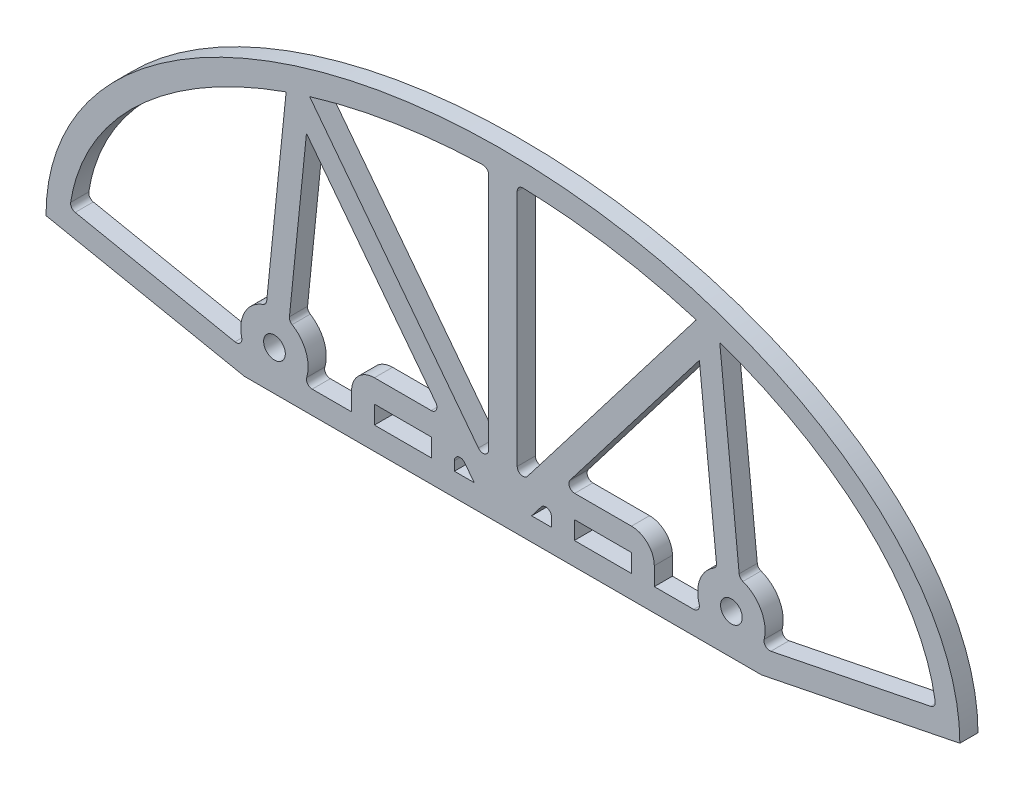
SolidWorks part; units mm, degrees
material "Birch Plywood"
ref_plane "Front Plane" through (0, 0, 0) normal (0, 0, 1) x (1, 0, 0)
ref_plane "Top Plane" through (0, 0, 0) normal (0, 1, 0) x (1, 0, 0)
ref_plane "Right Plane" through (0, 0, 0) normal (1, 0, 0) x (0, 0, -1)
sketch "Sketch3" plane through (0, 0, 0) normal (0, 0, 1) x (1, 0, 0)
  line L0 (85.2659, 27.2) -> (74.7341, 27.2) construction
  line L1 (74.7341, 27.2) -> (74.7341, 15.2) construction
  line L2 (74.7341, 15.2) -> (85.2659, 15.2) construction
  line L3 (85.2659, 15.2) -> (85.2659, 27.2) construction
  line L4 (5.2659, 27.2) -> (-5.2659, 27.2) construction
  line L5 (-5.2659, 27.2) -> (-5.2659, 15.2) construction
  line L6 (-5.2659, 15.2) -> (5.2659, 15.2) construction
  line L7 (5.2659, 15.2) -> (5.2659, 27.2) construction
  line L8 (85.2659, 27.2) -> (74.7341, 27.2) construction
  line L9 (74.7341, 27.2) -> (74.7341, 15.2) construction
  line L10 (74.7341, 15.2) -> (85.2659, 15.2) construction
  line L11 (85.2659, 15.2) -> (85.2659, 27.2) construction
  line L12 (5.2659, 27.2) -> (-5.2659, 27.2) construction
  line L13 (-5.2659, 27.2) -> (-5.2659, 15.2) construction
  line L14 (-5.2659, 15.2) -> (5.2659, 15.2) construction
  line L15 (5.2659, 15.2) -> (5.2659, 27.2) construction
  line L16 (0, 22.2) -> (80, 22.2) construction
  line L17 (-40, 22.2) -> (0, 22.2) construction
  line L18 (80, 22.2) -> (120, 22.2) construction
  line L19 (-40, 22.2) -> (-40, 72.2) construction
  line L20 (-40, 72.2) -> (40, 72.2) construction
  line L21 (-40, 22.2) -> (-5.2659, 15.2)
  line L22 (-5.2659, 15.2) -> (85.2659, 15.2)
  line L23 (85.2659, 15.2) -> (120, 22.2)
  line L24 (40, 72.2) -> (40, 15.2) construction
  line L25 (52.5, 22.375) -> (52.5, 19.2)
  line L26 (17.5, 22.375) -> (27.5, 22.375)
  line L27 (17.5, 22.375) -> (17.5, 19.2)
  line L28 (17.5, 19.2) -> (27.5, 19.2)
  line L29 (27.5, 22.375) -> (27.5, 19.2)
  line L30 (62.5, 19.2) -> (52.5, 19.2)
  line L31 (62.5, 22.375) -> (62.5, 19.2)
  line L32 (62.5, 22.375) -> (52.5, 22.375)
  circle A0 centre (80, 22.2) radius 1.9 construction
  circle A1 centre (0, 22.2) radius 1.9 construction
  circle A2 centre (80, 22.2) radius 1.9
  circle A3 centre (0, 22.2) radius 1.9
  ellipse E0 centre (40, 22.2) end of major axis (-40, 22.2) minor radius 50 (120, 22.2) -> (-40, 22.2) ccw
  dimension "D1" = 50
  dimension "D2" = 80
  dimension "D3" = 10
  dimension "D4" = 3.175
  dimension "D5" = 4
  dimension "D6" = 25
extrude "Boss-Extrude1" add sketch "Sketch3" along normal blind 3.175
sketch "Sketch4" plane through (0, 0, 3.175) normal (0, 0, 1) x (1, 0, 0)
  line L0 (-35.8077, 25.4355) -> (-5.1088, 19.2488)
  line L1 (5.0804, 19.2) -> (74.9196, 19.2)
  line L2 (85.1088, 19.2488) -> (115.8077, 25.4355)
  line L3 (85.2659, 15.2) -> (120, 22.2)
  line L4 (52.5, 22.375) -> (52.5, 19.2)
  line L5 (62.5, 22.375) -> (52.5, 22.375)
  line L6 (62.5, 19.2) -> (62.5, 22.375)
  line L7 (52.5, 19.2) -> (62.5, 19.2)
  line L8 (52.5, 22.375) -> (52.5, 19.2) construction
  line L9 (62.5, 22.375) -> (52.5, 22.375) construction
  line L10 (62.5, 19.2) -> (62.5, 22.375) construction
  line L11 (52.5, 19.2) -> (62.5, 19.2) construction
  line L12 (17.5, 19.2) -> (27.5, 19.2)
  line L13 (17.5, 22.375) -> (17.5, 19.2)
  line L14 (27.5, 22.375) -> (17.5, 22.375)
  line L15 (27.5, 19.2) -> (27.5, 22.375)
  line L16 (17.5, 19.2) -> (27.5, 19.2) construction
  line L17 (17.5, 22.375) -> (17.5, 19.2) construction
  line L18 (27.5, 22.375) -> (17.5, 22.375) construction
  line L19 (27.5, 19.2) -> (27.5, 22.375) construction
  line L20 (-40, 22.2) -> (-5.2659, 15.2)
  line L21 (-5.2659, 15.2) -> (85.2659, 15.2)
  line L22 (85.2659, 15.2) -> (120, 22.2) construction
  line L23 (-40, 22.2) -> (-5.2659, 15.2) construction
  line L24 (-5.2659, 15.2) -> (85.2659, 15.2) construction
  line L25 (17.5, 26.375) -> (27.5, 26.375)
  line L26 (13.5, 22.375) -> (13.5, 19.2)
  line L27 (31.5, 22.375) -> (31.5, 19.2)
  line L28 (40, 15.2) -> (40, 72.2) construction
  line L29 (48.5, 22.375) -> (48.5, 19.2)
  line L30 (62.5, 26.375) -> (52.5, 26.375)
  line L31 (66.5, 22.375) -> (66.5, 19.2)
  line L32 (-4.8669, 19.2) -> (84.8669, 19.2) construction
  line L33 (-35.8077, 25.4355) -> (-4.8669, 19.2) construction
  line L34 (84.8669, 19.2) -> (115.8077, 25.4355) construction
  line L35 (37.5, 68.2) -> (42.5, 68.2)
  line L36 (37.5, 68.2) -> (37.5, 19.2)
  line L37 (37.5, 19.2) -> (42.5, 19.2)
  line L38 (42.5, 68.2) -> (42.5, 19.2)
  line L39 (4.1233, 62.6899) -> (37.5, 19.2) construction
  line L40 (2.123, 62.0112) -> (34.9789, 19.2)
  line L41 (37.5, 22.485) -> (6.1527, 63.3306)
  line L42 (18.551, 40.6056) -> (21.7242, 43.0409) construction
  line L43 (0, 22.2) -> (4.1233, 62.6899) construction
  line L44 (2.0409, 61.9824) -> (-1.4274, 27.9247)
  line L45 (2.5521, 27.5195) -> (6.1935, 63.2774)
  line L46 (0.3068, 44.9535) -> (4.2862, 44.5483) construction
  line L47 (42.5, 19.2) -> (75.8767, 62.6899) construction
  line L48 (75.8767, 62.6899) -> (80, 22.2) construction
  line L49 (73.8473, 63.3306) -> (42.5, 22.485)
  line L50 (45.0211, 19.2) -> (77.877, 62.0112)
  line L51 (77.4479, 27.5195) -> (73.7996, 63.3451)
  line L52 (81.4274, 27.9247) -> (77.9591, 61.9824)
  line L53 (58.1737, 42.9078) -> (61.3469, 40.4725) construction
  line L54 (79.6932, 44.9535) -> (75.7138, 44.5483) construction
  line L55 (6.1935, 63.2774) -> (6.2004, 63.3451)
  arc A0 (85.1088, 19.2488) -> (74.9196, 19.2) centre (80, 22.2) ccw
  circle A1 centre (80, 22.2) radius 1.9
  circle A2 centre (80, 22.2) radius 1.9 construction
  circle A3 centre (0, 22.2) radius 1.9
  circle A4 centre (0, 22.2) radius 1.9 construction
  arc A5 (5.0804, 19.2) -> (-5.1088, 19.2488) centre (0, 22.2) ccw
  circle A7 centre (0, 22.2) radius 5.9 construction
  circle A8 centre (80, 22.2) radius 5.9 construction
  arc A10 (17.5, 26.375) -> (13.5, 22.375) centre (17.5, 22.375) ccw
  arc A11 (31.5, 22.375) -> (27.5, 26.375) centre (27.5, 22.375) ccw
  arc A12 (48.5, 22.375) -> (52.5, 26.375) centre (52.5, 22.375) cw
  arc A13 (62.5, 26.375) -> (66.5, 22.375) centre (62.5, 22.375) cw
  arc A14 (28.2377, 27.9838) -> (27.4444, 26.375) centre (27.4444, 27.375) cw
  arc A15 (33.2933, 21.3963) -> (31.5, 20.7875) centre (32.5, 20.7875) ccw
  arc A16 (48.5, 20.7875) -> (46.7067, 21.3963) centre (47.5, 20.7875) ccw
  arc A17 (52.5556, 26.375) -> (51.7623, 27.9838) centre (52.5556, 27.375) cw
  ellipse E1 centre (40, 22.2) end of major axis (-40, 22.2) minor radius 50 (120, 22.2) -> (-40, 22.2) ccw
  ellipse E2 centre (40, 22.2) end of major axis (-40, 22.2) minor radius 50 (120, 22.2) -> (-40, 22.2) ccw construction
  spline S0 degree 1 poles (115.8077, 25.4355) (-35.8077, 25.4355) knots 0 0 1 1 construction
  spline S1 degree 3 poles (115.8077, 25.4355) (115.6445, 26.8071) (115.1196, 29.5011) (113.2412, 34.9033) (109.3338, 41.5165) (102.177, 48.9647) (91.951, 56.1358) (83.1998, 60.1358) (77.9454, 61.9872) (77.9181, 61.9968) (77.8907, 62.0064) (77.6255, 62.0996) (77.1208, 62.2745) (76.2937, 62.5539) (75.4596, 62.8269) (74.6188, 63.0936) (74.105, 63.2522) (73.8394, 63.333) (73.8235, 63.3378) (73.8076, 63.3427) (71.9958, 63.8929) (63.5411, 66.2046) (49.7109, 68.2708) (30.2891, 68.2708) (16.4589, 66.2046) (8.0042, 63.8929) (6.1924, 63.3427) (6.1765, 63.3378) (6.1606, 63.333) (5.895, 63.2522) (5.3812, 63.0936) (4.5404, 62.8269) (3.7063, 62.5539) (2.8792, 62.2745) (2.3745, 62.0996) (2.1093, 62.0064) (2.0819, 61.9968) (2.0546, 61.9872) (-3.1998, 60.1358) (-11.951, 56.1358) (-22.177, 48.9647) (-29.3338, 41.5165) (-33.2412, 34.9033) (-35.1196, 29.5011) (-35.6445, 26.8071) (-35.8077, 25.4355) knots 3.215824 3.215824 3.215824 3.215824 3.309359 3.402895 3.589965 3.777036 3.964107 4.198724 4.199337 4.199644 4.199951 4.200564 4.211521 4.222479 4.237253 4.248247 4.259241 4.259585 4.259757 4.259929 4.260274 4.338248 4.618854 4.805924 5.08653 5.164504 5.164849 5.165021 5.165193 5.165537 5.176531 5.187525 5.202299 5.213257 5.224214 5.224827 5.225134 5.225441 5.226054 5.460671 5.647742 5.834813 6.021883 6.115419 6.208954 6.208954 6.208954 6.208954
  point P42 (85.9, 22.2)
  point P43 (5.9, 22.2)
  point P53 (40, 19.2)
  point P54 (40, 68.2)
  point P68 (20.1376, 41.8233)
  point P75 (2.2965, 44.7509)
  point P79 (59.7603, 41.6901)
  point P82 (77.7035, 44.7509)
  dimension "D7" = 4
  dimension "D10" = 4
  dimension "D14" = 1
  dimension "D9" = 5
  dimension "D11" = 4
  dimension "D12" = 4
  dimension "D13" = 4
  dimension "D1" = 0
  dimension "D2" = 0
  dimension "D3" = 0
  dimension "D4" = 0
  dimension "D5" = 0
  dimension "D6" = 4
  dimension "D8" = 4
extrude "Cut-Extrude2" cut sketch "Sketch4" against normal up to surface (3.175 mm away) contours L44 S1 L0 A5 | A14 L40 L45 A5 L1 L26 A10 L25 | L36 S1 L55 L41 | L40 A15 L27 L1 | L51 S1 L38 L49 | L29 A16 L50 L1 | A17 L30 A13 L31 L1 A0 L51 L50 | L2 S1 L52 A0 up to face at (57.5, 20.7875, 0)
fillet "Fillet1" radius 1 14 edges at (115.8077, 25.4355, 1.5875) (-35.8077, 25.4355, 1.5875) (-5.1088, 19.2488, 1.5875) (5.0804, 19.2, 1.5875) (2.5521, 27.5195, 1.5875) (-1.4274, 27.9247, 1.5875) (37.5, 22.485, 1.5875) (37.5, 68.1747, 1.5875) (42.5, 68.1747, 1.5875) (42.5, 22.485, 1.5875) (85.1088, 19.2488, 1.5875) (81.4274, 27.9247, 1.5875) (74.9196, 19.2, 1.5875) (77.4479, 27.5195, 1.5875)
equation "\"prop-dist\"= 80mm"
equation "\"prop-hole-depth\"= 9mm"
equation "\"prop-hole-diameter\"= 11mm"
equation "\"rivet-extension\"= 12mm"
equation "\"rivet-hole-extension\"= 7mm"
equation "\"rivet-hole-diameter\"= 3.8mm"
equation "\"ski-length\"= 100mm"
equation "\"th\"= 0.125in'material thickness"
equation "\"ski-height\"= 50mm"
equation "\"ski-curve-gap\"= 80mm"
equation "\"ski-curve-height\"= \"rivet-hole-extension\""
equation "\"min-width\"= 4mm"
equation "\"prop-hole-diameter-small\"= 8.6mm"
equation "\"prop-dist-width\"= 86.5mm"
equation "\"prop-dist-length\"= 80mm"
equation "\"prop-boost\"= 4.4mm"
equation "\"back-drop\"= 5mm"
equation "\"T\"= 0.125in'Material Thickness"
equation "\"tof_c2c\"= 19.9mm'Center to center distance of TOF sensor holes"
equation "\"tof_d\"= 3mm'TOF hole diameter"
equation "\"tof_w\"= 12.6mm'TOF width"
equation "\"tof_l\"= 15.6mm'TOF length"
equation "\"pin_w\"= 2.3mm'A standard IO Pin socket width"
equation "\"pin_l\"= 2.5mm'A standard IO Pin socket length"
equation "\"esp_pin_num\"= 8'Number of pins on one side of the ESP"
equation "\"esp_l\"= 40mm'ESP length"
equation "\"esp_w\"= 27mm'ESP width"
equation "\"esp_pin_inset\"= 3mm'Distance that ESP pins are inset"
equation "\"bat_l\"= 27mm'Battery length"
equation "\"bat_w\"= 20mm'Battery width"
equation "\"bat_h\"= 6mm'Battery thickness"
equation "\"boost_w\"= 17.2mm"
equation "\"boost_l\"= 37mm"
equation "\"boost_hole_inset\"= 2.2mm"
equation "\"boost_hole_dist\"= 7mm"
equation "\"boost_hole_d\"= 2mm"
equation "\"support_width\"= 10mm"
equation "\"support_gap\"= 25mm"
equation "\"D1@Sketch3\"=\"ski-height\""
equation "\"D2@Sketch3\"=\"ski-curve-gap\""
equation "\"D3@Sketch3\"=\"support_width\""
equation "\"D4@Sketch3\"=\"T\""
equation "\"D6@Sketch3\"=\"support_gap\""
equation "\"D1@Boss-Extrude1\"=\"T\""
equation "\"support_height\"= 21.5mm"
